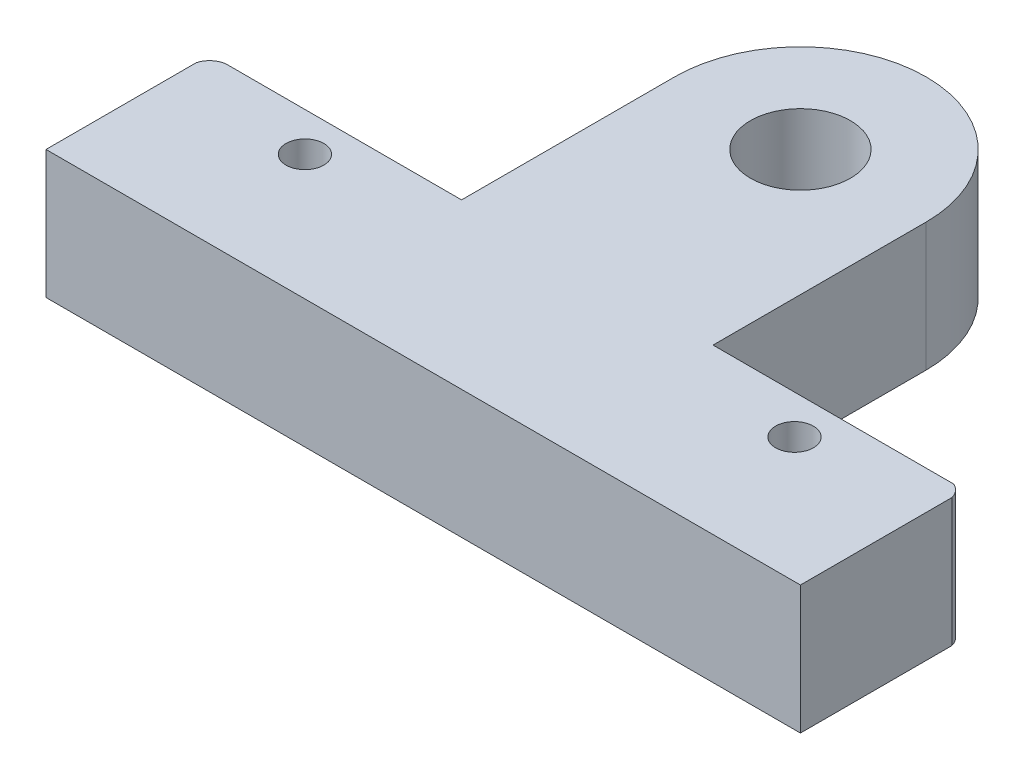
SolidWorks part; units mm, degrees
ref_plane "Alzado" through (0, 0, 0) normal (0, 0, 1) x (1, 0, 0)
ref_plane "Planta" through (0, 0, 0) normal (0, 1, 0) x (1, 0, 0)
ref_plane "Vista lateral" through (0, 0, 0) normal (1, 0, 0) x (0, 0, -1)
sketch "Croquis1" plane through (0, 0, 0) normal (0, 1, 0) x (1, 0, 0)
  line L0 (-15.3641, 6.4865) -> (-15.3641, -6.5633) construction
  line L1 (-34.1024, 6.4865) -> (-15.3641, 6.4865)
  line L2 (-35.3641, 5.3864) -> (-35.3641, -6.5633)
  line L3 (-35.3641, -6.5633) -> (24.6359, -6.5633)
  line L4 (24.6359, 5.4846) -> (24.6359, -6.5633)
  line L5 (4.6359, 6.4865) -> (23.7686, 6.4865)
  line L6 (4.6359, 6.4865) -> (4.6359, -6.5633) construction
  line L7 (-15.3641, 6.4865) -> (-15.3641, 23.4367)
  line L9 (4.6359, 6.4865) -> (4.6359, 23.4367)
  circle A0 centre (-5.3641, 23.4367) radius 3.975
  arc A1 (4.6359, 23.4367) -> (-15.3641, 23.4367) centre (-5.3641, 23.4367) ccw
  arc A2 (24.6359, 5.4846) -> (23.7686, 6.4865) centre (23.1848, 5.1048) ccw
  arc A3 (-34.1024, 6.4865) -> (-35.3641, 5.3864) centre (-33.9152, 4.9983) ccw
  circle A4 centre (-24.7333, 3.398) radius 1.5
  circle A5 centre (14.2023, 3.398) radius 1.5
  dimension "D1" = 7.95
  dimension "D2" = 20
  dimension "D3" = 20
  dimension "D4" = 20
  dimension "D5" = 10
  dimension "D6" = 30
extrude "Saliente-Extruir1" add sketch "Croquis1" along normal blind 10.2
